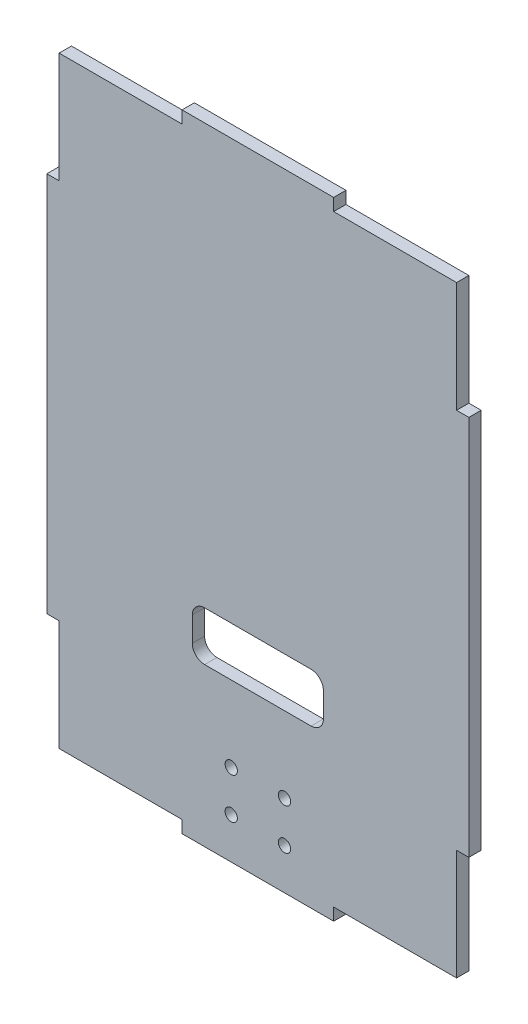
SolidWorks part; units mm, degrees
ref_plane "Plano frontal" through (0, 0, 0) normal (0, 0, 1) x (1, 0, 0)
ref_plane "Plano superior" through (0, 0, 0) normal (0, 1, 0) x (1, 0, 0)
ref_plane "Plano direito" through (0, 0, 0) normal (1, 0, 0) x (0, 0, -1)
sketch "Esboço1" plane through (0, 0, 0) normal (0, 0, 1) x (1, 0, 0)
  line L1 (-51.5, -76.5) -> (51.5, -76.5)
  line L2 (-51.5, -76.5) -> (-51.5, 76.5)
  line L3 (-51.5, 76.5) -> (51.5, 76.5)
  line L4 (51.5, -76.5) -> (51.5, 76.5)
  line L5 (-51.5, -76.5) -> (51.5, 76.5) construction
  line L6 (-51.5, 76.5) -> (51.5, -76.5) construction
  point P0 (0, 0)
  dimension "D1" = 103
  dimension "D2" = 153
extrude "Ressalto-extrusão1" add sketch "Esboço1" along normal blind 3
sketch "Esboço2" plane through (0, 0, 3) normal (0, 0, 1) x (1, 0, 0)
  line L1 (-16, -38) -> (16, -38)
  line L2 (-16, -38) -> (-16, -26)
  line L3 (-16, -26) -> (16, -26)
  line L4 (16, -38) -> (16, -26)
  line L5 (-16, -38) -> (16, -26) construction
  line L6 (-16, -26) -> (16, -38) construction
  point P0 (0, -32)
  dimension "D1" = 12
  dimension "D2" = 32
  dimension "D3" = 32
extrude "Corte-extrusão1" cut sketch "Esboço2" against normal through all
fillet "Filete1" radius 3 4 edges at (16, -38, 1.5) (16, -26, 1.5) (-16, -38, 1.5) (-16, -26, 1.5)
sketch "Esboço3" plane through (0, 0, 0) normal (0, 0, -1) x (-1, 0, 0)
  line L0 (51.5, 76.5) -> (51.5, -76.5) construction
  line L1 (-51.5, -76.5) -> (51.5, -76.5)
  line L2 (-51.5, -76.5) -> (-51.5, -73.5)
  line L3 (-51.5, -73.5) -> (51.5, -73.5)
  line L4 (51.5, -76.5) -> (51.5, -73.5)
  line L5 (-18.5, -73.5) -> (-18.5, -76.5)
  line L6 (18.5, -73.5) -> (18.5, -76.5)
  line L7 (-66.3107, 0) -> (74.8748, 0) construction
  line L8 (18.5, 73.5) -> (18.5, 76.5)
  line L9 (-18.5, 73.5) -> (-18.5, 76.5)
  line L10 (51.5, 76.5) -> (51.5, 73.5)
  line L11 (-51.5, 73.5) -> (51.5, 73.5)
  line L12 (-51.5, 76.5) -> (-51.5, 73.5)
  line L13 (-51.5, 76.5) -> (51.5, 76.5)
  line M10 (-51.5, 76.5) -> (-51.5, -76.5)
  line M11 (-51.5, -76.5) -> (51.5, -76.5)
  line M12 (51.5, -76.5) -> (51.5, 76.5)
  line M13 (51.5, 76.5) -> (-51.5, 76.5)
  dimension "D1" = 3
  dimension "D2" = 33
  dimension "D3" = 33
extrude "Corte-extrusão2" cut sketch "Esboço3" against normal through all contours L3 L6 M11 M12 | L5 L3 M10 M11 | L8 L11 M12 M13 | L11 L9 M10 M13
sketch "Esboço4" plane through (0, 0, 0) normal (0, 0, -1) x (-1, 0, 0)
  line L0 (0, -52.6809) -> (0, -80.3191) construction
  line L1 (18.5, -73.5) -> (51.5, -73.5) construction
  line L2 (51.5, 73.5) -> (48.5, 73.5)
  line L3 (51.5, 73.5) -> (51.5, -73.5)
  line L4 (51.5, -73.5) -> (48.5, -73.5)
  line L5 (48.5, 73.5) -> (48.5, -73.5)
  line L6 (48.5, 46.5) -> (51.5, 46.5)
  line L7 (48.5, -46.5) -> (51.5, -46.5)
  line L8 (-48.5, -46.5) -> (-51.5, -46.5)
  line L9 (-48.5, 46.5) -> (-51.5, 46.5)
  line L10 (-48.5, 73.5) -> (-48.5, -73.5)
  line L11 (-51.5, -73.5) -> (-48.5, -73.5)
  line L12 (-51.5, 73.5) -> (-51.5, -73.5)
  line L13 (-51.5, 73.5) -> (-48.5, 73.5)
  line L14 (18.5, -76.5) -> (-18.5, -76.5) construction
  line L15 (-6.5, -66.5) -> (6.5, -66.5) construction
  circle A0 centre (-6.5, -66.5) radius 1.5
  circle A1 centre (-6.5, -56.5) radius 1.5
  circle A2 centre (6.5, -66.5) radius 1.5
  circle A3 centre (6.5, -56.5) radius 1.5
  point P30 (0, -66.5)
  dimension "D4" = 3
  dimension "D1" = 3
  dimension "D2" = 27
  dimension "D3" = 27
  dimension "D5" = 10
  dimension "D6" = 10
  dimension "D7" = 6.5
extrude "Corte-extrusão3" cut sketch "Esboço4" against normal through all
